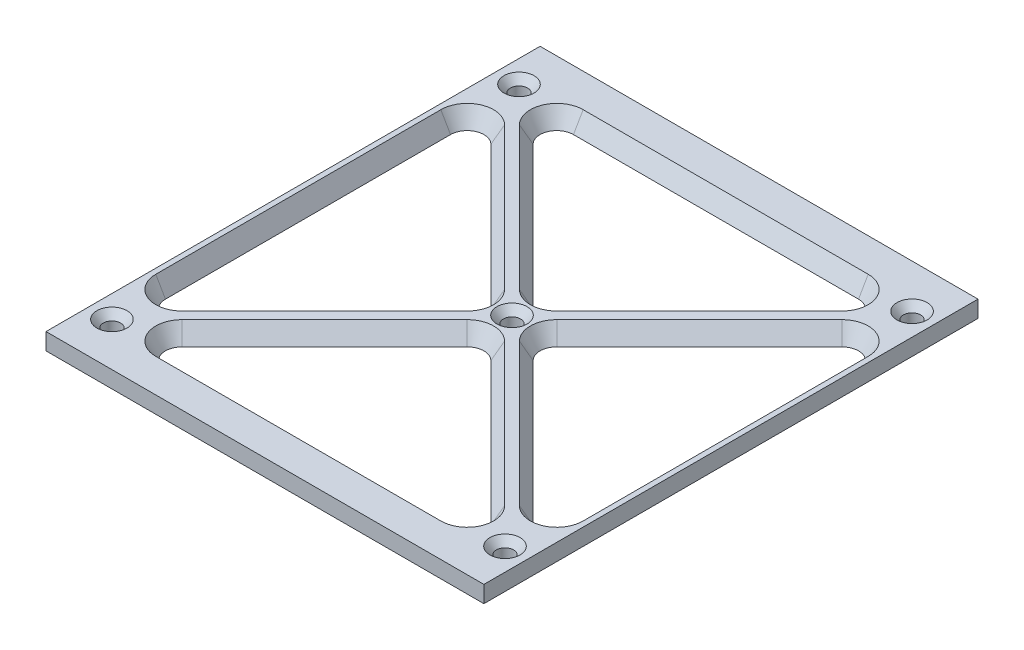
SolidWorks part; units mm, degrees
ref_plane "Front Plane" through (0, 0, 0) normal (0, 0, 1) x (1, 0, 0)
ref_plane "Top Plane" through (0, 0, 0) normal (0, 1, 0) x (1, 0, 0)
ref_plane "Right Plane" through (0, 0, 0) normal (1, 0, 0) x (0, 0, -1)
sketch "Sketch1" plane through (0, 0, 0) normal (0, 1, 0) x (1, 0, 0)
  line L1 (-41.5, -46.825) -> (41.5, -46.825)
  line L2 (-41.5, -46.825) -> (-41.5, 46.825)
  line L3 (-41.5, 46.825) -> (41.5, 46.825)
  line L4 (41.5, -46.825) -> (41.5, 46.825)
  line L5 (-41.5, -46.825) -> (41.5, 46.825) construction
  line L6 (-41.5, 46.825) -> (41.5, -46.825) construction
  point P0 (0, 0)
  dimension "D1" = 83
  dimension "D2" = 93.65
extrude "Boss-Extrude1" add sketch "Sketch1" along normal blind 3.175
hole_wizard "CSK for #4 Flat Head Machine Screw1" positions "Sketch3" profile "Sketch2" countersink size "#4" standard "ANSI Inch" end condition through all
sketch "Sketch3" plane through (0, 3.175, 0) normal (0, 1, 0) x (1, 0, 0)
  circle A0 centre (37.25, 38.575) radius 1.4732 construction
  circle A1 centre (37.25, -38.575) radius 1.4732 construction
  circle A2 centre (-37.25, 38.575) radius 1.4732 construction
  circle A3 centre (-37.25, -38.575) radius 1.4732 construction
  point P0 (37.25, 38.575)
  point P2 (37.25, -38.575)
  point P4 (-37.25, -38.575)
  point P6 (-37.25, 38.575)
sketch "Sketch2" plane through (37.25, 3.175, -38.575) normal (1, 0, 0) x (0, 0, 1)
  line L0 (0, 0) -> (0, 3.175)
  line L1 (0, 3.175) -> (1.6319, 3.175)
  line L2 (1.6319, 3.175) -> (1.6319, 1.4098)
  line L3 (1.6319, 1.4098) -> (2.8575, 0)
  line L5 (2.8575, 0) -> (0, 0)
  line L6 (-1.632, 1.4098) -> (-2.8575, 0) construction
  line L11 (0, -6.35) -> (0, 107.95) construction
  dimension "Thru Hole Dia." = 3.2639
  dimension "Thru Hole Depth" = 3.175
  dimension "Near C'Sink Dia." = 5.715
  dimension "Near C'Sink Angle" = 82
sketch "Sketch4" plane through (0, 3.175, 0) normal (0, 1, 0) x (1, 0, 0)
  line L0 (-40.5, 27.0147) -> (-40.5, -27.0147)
  line L1 (-27.0147, -40.5) -> (27.0147, -40.5)
  line L2 (40.5, -27.0147) -> (40.5, 27.0147)
  line L3 (-27.0147, 40.5) -> (27.0147, 40.5)
  line L6 (-35.5, -35.5) -> (35.5, 35.5) construction
  line L7 (35.5, -35.5) -> (-35.5, 35.5) construction
  line L8 (-30.5503, -31.9645) -> (-3.5355, -4.9497)
  line L9 (30.5503, -31.9645) -> (3.5355, -4.9497)
  line L10 (-31.9645, -30.5503) -> (-4.9497, -3.5355)
  line L11 (31.9645, -30.5503) -> (4.9497, -3.5355)
  line L12 (4.9497, 3.5355) -> (31.9645, 30.5503)
  line L13 (-4.9497, 3.5355) -> (-31.9645, 30.5503)
  line L14 (-3.5355, 4.9497) -> (-30.5503, 31.9645)
  line L15 (3.5355, 4.9497) -> (30.5503, 31.9645)
  line L16 (-41.5, 46.825) -> (-41.5, -46.825) construction
  line L17 (-35.5, -35.5) -> (35.5, -35.5) construction
  line L18 (-35.5, -35.5) -> (-35.5, 35.5) construction
  line L19 (-35.5, 35.5) -> (35.5, 35.5) construction
  line L20 (35.5, -35.5) -> (35.5, 35.5) construction
  arc A0 (-30.5503, -31.9645) -> (-27.0147, -40.5) centre (-27.0147, -35.5) ccw
  arc A1 (-31.9645, -30.5503) -> (-40.5, -27.0147) centre (-35.5, -27.0147) cw
  arc A2 (-40.5, 27.0147) -> (-31.9645, 30.5503) centre (-35.5, 27.0147) cw
  arc A3 (-27.0147, 40.5) -> (-30.5503, 31.9645) centre (-27.0147, 35.5) ccw
  arc A4 (40.5, 27.0147) -> (31.9645, 30.5503) centre (35.5, 27.0147) ccw
  arc A5 (27.0147, 40.5) -> (30.5503, 31.9645) centre (27.0147, 35.5) cw
  arc A6 (-3.5355, 4.9497) -> (3.5355, 4.9497) centre (0, 8.4853) ccw
  arc A7 (-4.9497, 3.5355) -> (-4.9497, -3.5355) centre (-8.4853, 0) cw
  arc A8 (-3.5355, -4.9497) -> (3.5355, -4.9497) centre (0, -8.4853) cw
  arc A9 (4.9497, 3.5355) -> (4.9497, -3.5355) centre (8.4853, 0) ccw
  arc A10 (31.9645, -30.5503) -> (40.5, -27.0147) centre (35.5, -27.0147) ccw
  arc A11 (30.5503, -31.9645) -> (27.0147, -40.5) centre (27.0147, -35.5) cw
  point P2 (0, 0)
  dimension "D1" = 5
  dimension "D2" = 1
  dimension "D4" = 2
  dimension "D5" = 2
extrude "Cut-Extrude1" cut sketch "Sketch4" against normal through all draft 30
hole_wizard "CSK for #4 Flat Head Machine Screw2" positions "Sketch6" profile "Sketch5" countersink size "#4" standard "ANSI Inch" end condition through all
sketch "Sketch6" plane through (0, 3.175, 0) normal (0, 1, 0) x (1, 0, 0)
  point P0 (0, 0)
sketch "Sketch5" plane through (0, 3.175, 0) normal (1, 0, 0) x (0, 0, 1)
  line L0 (0, 0) -> (0, 3.175)
  line L1 (0, 3.175) -> (1.6319, 3.175)
  line L2 (1.6319, 3.175) -> (1.6319, 1.4098)
  line L3 (1.6319, 1.4098) -> (2.8575, 0)
  line L5 (2.8575, 0) -> (0, 0)
  line L6 (-1.6319, 1.4098) -> (-2.8575, 0) construction
  line L11 (0, -6.35) -> (0, 107.95) construction
  dimension "Thru Hole Dia." = 3.2639
  dimension "Thru Hole Depth" = 3.175
  dimension "Near C'Sink Dia." = 5.715
  dimension "Near C'Sink Angle" = 82
